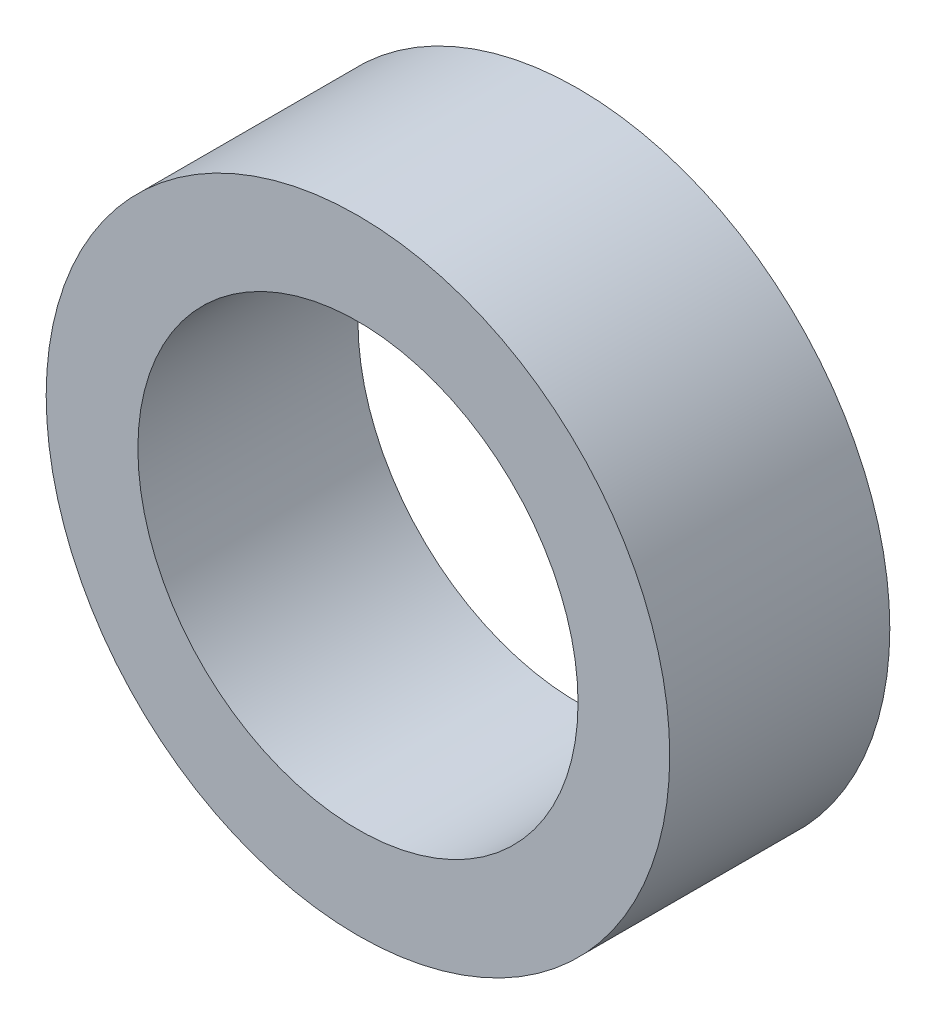
SolidWorks part; units mm, degrees
ref_plane "Front Plane" through (0, 0, 0) normal (0, 0, 1) x (1, 0, 0)
ref_plane "Top Plane" through (0, 0, 0) normal (0, 1, 0) x (1, 0, 0)
ref_plane "Right Plane" through (0, 0, 0) normal (1, 0, 0) x (0, 0, -1)
sketch "Sketch1" plane through (0, 0, 0) normal (0, 0, 1) x (1, 0, 0)
  circle A0 centre (0, 0) radius 17
  circle A1 centre (0, 0) radius 12
  dimension "D1" = 34
  dimension "D2" = 24
extrude "Boss-Extrude1" add sketch "Sketch1" against normal blind 12
